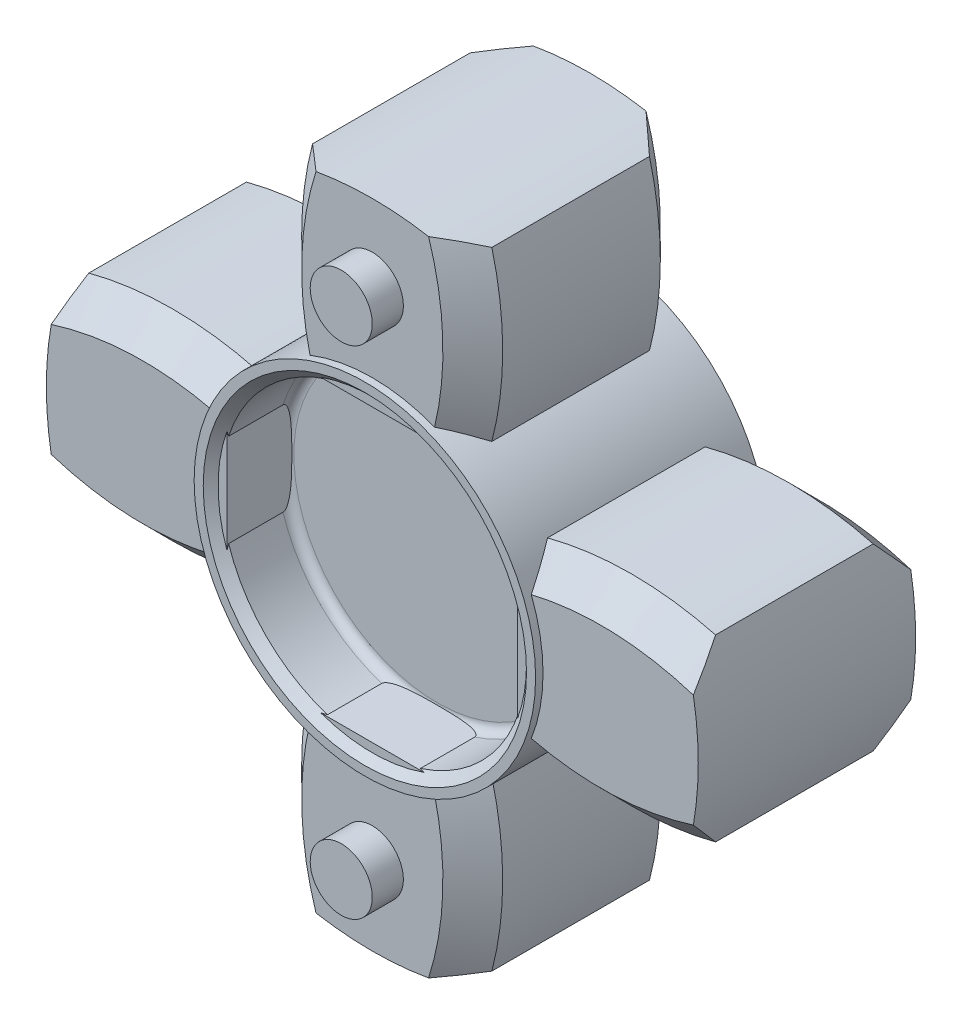
SolidWorks part; units mm, degrees
ref_plane "Front Plane" through (0, 0, 0) normal (0, 0, 1) x (1, 0, 0)
ref_plane "Top Plane" through (0, 0, 0) normal (0, 1, 0) x (1, 0, 0)
ref_plane "Right Plane" through (0, 0, 0) normal (1, 0, 0) x (0, 0, -1)
sketch "Sketch1" plane through (0, 0, 0) normal (0, 0, 1) x (1, 0, 0)
  line L0 (0, 0) -> (0, 16.6688) construction
  line L1 (-4.5847, 16.0258) -> (4.5847, 16.0258) construction
  line L2 (0, 16.6688) -> (0, 8.7312) construction
  line L3 (16.0258, 4.5847) -> (16.0258, -4.5847) construction
  line L4 (16.6687, 0) -> (8.7312, 0) construction
  line L5 (4.5847, -16.0258) -> (-4.5847, -16.0258) construction
  line L6 (0, -16.6688) -> (0, -8.7312) construction
  line L7 (-16.0258, -4.5847) -> (-16.0258, 4.5847) construction
  line L8 (-16.6687, 0) -> (-8.7312, 0) construction
  line L9 (0, 0) -> (12.7, 0) construction
  circle A0 centre (0, 0) radius 16.6687 construction
  circle A1 centre (0, 0) radius 8.7312 construction
  arc A2 (-4.5847, 16.0258) -> (-4.5847, 7.4307) centre (11.7767, 11.7283) ccw construction
  arc A3 (4.5847, 16.0258) -> (4.5847, 7.4307) centre (-11.7767, 11.7283) cw construction
  circle A4 centre (0, 0) radius 7.8016 construction
  arc A6 (16.0258, 4.5847) -> (7.4307, 4.5847) centre (11.7283, -11.7767) ccw construction
  arc A7 (16.0258, -4.5847) -> (7.4307, -4.5847) centre (11.7283, 11.7767) cw construction
  arc A9 (4.5847, -16.0258) -> (4.5847, -7.4307) centre (-11.7767, -11.7283) ccw construction
  arc A10 (-4.5847, -16.0258) -> (-4.5847, -7.4307) centre (11.7767, -11.7283) cw construction
  arc A12 (-16.0258, -4.5847) -> (-7.4307, -4.5847) centre (-11.7283, 11.7767) ccw construction
  arc A13 (-16.0258, 4.5847) -> (-7.4307, 4.5847) centre (-11.7283, -11.7767) cw construction
  circle A32 centre (0, 12.7) radius 1.5875 construction
  circle A33 centre (12.7, 0) radius 1.5875 construction
  circle A34 centre (0, 0) radius 12.7 construction
  point P7 (0, 16.6688)
  point P23 (16.6687, 0)
  point P34 (0, -16.6688)
  point P45 (-16.6687, 0)
  point P53 (0, 0)
  point P60 (0, 0)
  point P70 (0, 0)
  dimension "OD" = 33.3375
  dimension "Hub OD" = 17.4625
  dimension "Lug Radius" = 16.9164
  dimension "Pin Diameter" = 3.175
  dimension "Lug Width" = 9.1694
  dimension "D2" = 90
  dimension "Wall Thickness" = 0.9296
  dimension "Number of Lugs" = 4
sketch "Sketch2" plane through (0, 0, 0) normal (1, 0, 0) x (0, 0, -1)
  line L0 (-5.5588, 0) -> (5.5588, 0) construction
  line L2 (-5.9385, 0) -> (5.9385, 0) construction
  line L3 (-7.1463, 0) -> (7.1463, 0) construction
  line L4 (2.2327, 0) -> (-2.2327, 0)
  point P3 (0, 0)
  point P7 (0, 0)
  point P10 (0, 0)
  point P13 (0, 0)
  dimension "Lug Length" = 11.1176
  dimension "Hub Length" = 11.877
  dimension "Pin Length" = 14.2926
  dimension "Hollowout" = 3.7059
sketch "Sketch4" plane through (0, 0, 0) normal (0, 0, 1) x (1, 0, 0)
  circle A0 centre (0, 0) radius 8.7312 construction
  circle A1 centre (0, 0) radius 8.7312
  circle A2 centre (0, 0) radius 7.8016 construction
  circle A3 centre (0, 0) radius 7.8016
extrude "Boss-Extrude1" add sketch "Sketch4" along normal up to vertex (5.9385 mm away) and the other way up to vertex (5.9385 mm away) up to point (0, 0, 5.9385) other way up to point (0, 0, -5.9385)
sketch "Sketch5" plane through (0, 0, 0) normal (0, 0, 1) x (1, 0, 0)
  circle A0 centre (0, 0) radius 7.8016 construction
  circle A1 centre (0, 0) radius 7.8016
extrude "Boss-Extrude2" add sketch "Sketch5" along normal up to vertex (2.2327 mm away) and the other way up to vertex (2.2327 mm away) up to point (0, 0, 2.2327) other way up to point (0, 0, -2.2327)
fillet "Fillet1" radius 0.4648 2 edges at (7.8016, 0, -2.2327) (7.8016, 0, 2.2327)
chamfer "Chamfer1" distance 0.4648 angle 45 2 edges at (7.8016, 0, 5.9385) (7.8016, 0, -5.9385)
sketch "Sketch7" plane through (0, 0, 0) normal (0, 0, 1) x (1, 0, 0)
  line L2 (-4.5847, 7.4307) -> (4.5847, 7.4307)
  arc A0 (-4.5847, 16.0258) -> (-4.5847, 7.4307) centre (11.7767, 11.7283) ccw construction
  arc A1 (4.5847, 7.4307) -> (4.5847, 16.0258) centre (-11.7767, 11.7283) ccw construction
  arc A2 (-4.5847, 16.0258) -> (-4.5847, 7.4307) centre (11.7767, 11.7283) ccw
  arc A3 (4.5847, 7.4307) -> (4.5847, 16.0258) centre (-11.7767, 11.7283) ccw
  arc A4 (4.5847, 16.0258) -> (-4.5847, 16.0258) centre (0, 0) ccw
extrude "Boss-Extrude3" add sketch "Sketch7" along normal up to vertex (5.5588 mm away) and the other way up to vertex (5.5588 mm away) up to point (0, 0, 5.5588) other way up to point (0, 0, -5.5588)
chamfer "Chamfer2" distance 1.5282 angle 45 4 edges at (-5.1397, 11.7283, -5.5588) (5.1397, 11.7283, -5.5588) (-5.1397, 11.7283, 5.5588) (5.1397, 11.7283, 5.5588)
pattern_circular "CirPattern1" count 4 over 360 about axis through (0, 0, 0) along (0, 0, 1) of "Boss-Extrude3", "Chamfer2"
sketch "Sketch10" plane through (0, 0, 0) normal (0, 0, 1) x (1, 0, 0)
  circle A8 centre (0, 12.7) radius 1.5875 construction
  circle A9 centre (0, 12.7) radius 1.5875
  point P3 (0, 0)
  point P14 (0, 0)
extrude "Boss-Extrude6" add sketch "Sketch10" along normal up to vertex (7.1463 mm away) up to point (0, 0, 7.1463)
sketch "Sketch13" plane through (0, 0, 0) normal (0, 0, 1) x (1, 0, 0)
  circle A3 centre (12.7, 0) radius 1.5875 construction
  circle A4 centre (12.7, 0) radius 1.5875
extrude "Boss-Extrude7" add sketch "Sketch13" against normal up to vertex (7.1463 mm away) up to point (0, 0, -7.1463)
pattern_circular "CirPattern2" count 2 over 360 about axis through (0, 0, 0) along (0, 0, 1) of "Boss-Extrude6", "Boss-Extrude7"
equation "\"D1@Fillet1\"=\"Wall Thickness@Sketch1\"*.5"
equation "\"D1@Chamfer1\"=\"Wall Thickness@Sketch1\"/2"
equation "\"D1@Chamfer2\" = \"Lug Width@Sketch1\" / 6"
equation "\"D1@CirPattern1\"=\"Number of Lugs@Sketch1\""
equation "\"D2@Sketch1\"=360/\"Number of Lugs@Sketch1\""
equation "\"D1@CirPattern2\"=\"Number of Lugs@Sketch1\"/2"
